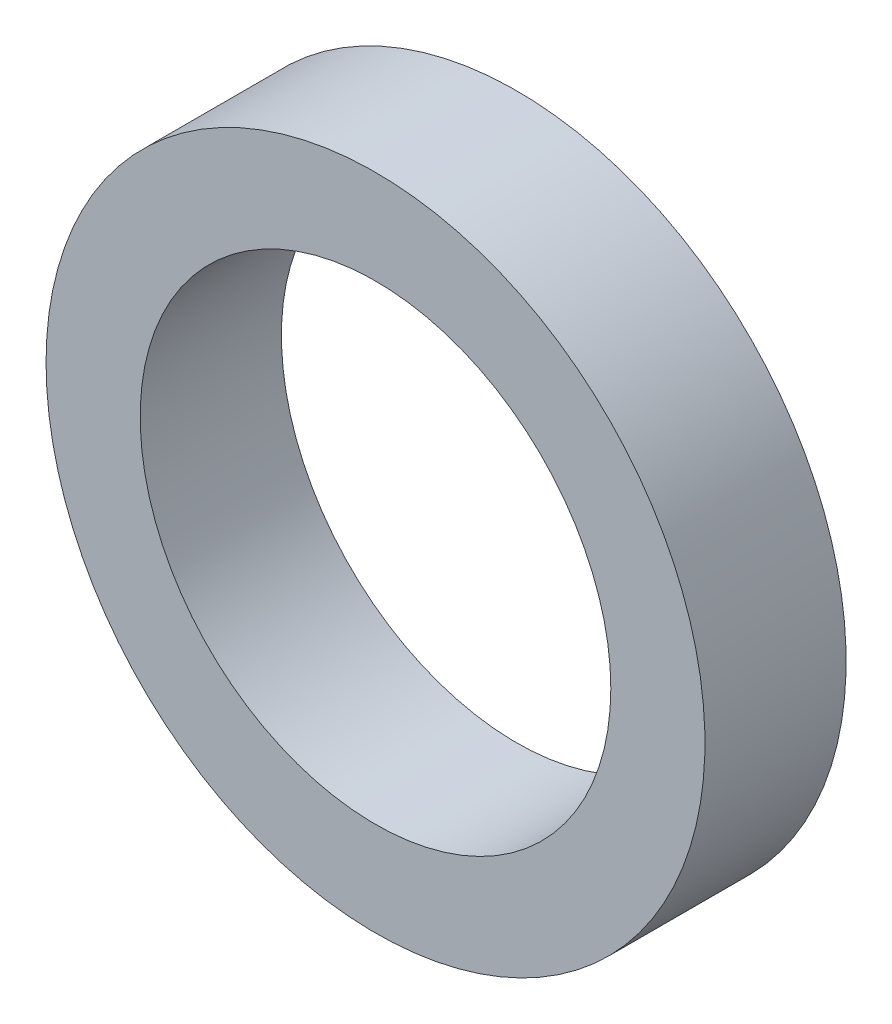
SolidWorks part; units mm, degrees
material "AISI 4130 Steel, annealed at 865C"
ref_plane "Front Plane" through (0, 0, 0) normal (0, 0, 1) x (1, 0, 0)
ref_plane "Top Plane" through (0, 0, 0) normal (0, 1, 0) x (1, 0, 0)
ref_plane "Right Plane" through (0, 0, 0) normal (1, 0, 0) x (0, 0, -1)
sketch "Sketch1" plane through (0, 0, 0) normal (0, 0, 1) x (1, 0, 0)
  circle A0 centre (0, 0) radius 11.1125
  circle A1 centre (0, 0) radius 6.35
  dimension "D1" = 22.225
  dimension "ID" = 12.7
extrude "Extrude1" add sketch "Sketch1" along normal mid plane 4.7625
sketch "Sketch2" plane through (0, 0, 0) normal (1, 0, 0) x (0, 0, -1)
  line L0 (-2.3813, -6.35) -> (2.3812, -6.35) construction
  line L3 (2.3812, 6.35) -> (-2.3813, 6.35) construction
  line L5 (-2.3813, -6.35) -> (2.3812, -6.35)
  line L6 (2.3812, 6.35) -> (-2.3813, 6.35)
sketch "Sketch4" plane through (0, 0, 2.3813) normal (0, 0, 1) x (1, 0, 0)
  line L0 (0, 0) -> (-4.4901, 4.4901)
  line L1 (0, -2.6194) -> (0, 2.6194) construction
  circle A0 centre (0, 0) radius 6.35 construction
  dimension "D1" = 45
sketch "Sketch5" plane through (0, 0, 2.3813) normal (0, 0, 1) x (1, 0, 0)
  circle A0 centre (0, 0) radius 7.9375
  dimension "D1" = 15.875
extrude "Cut-Extrude1" cut sketch "Sketch5" against normal through all
